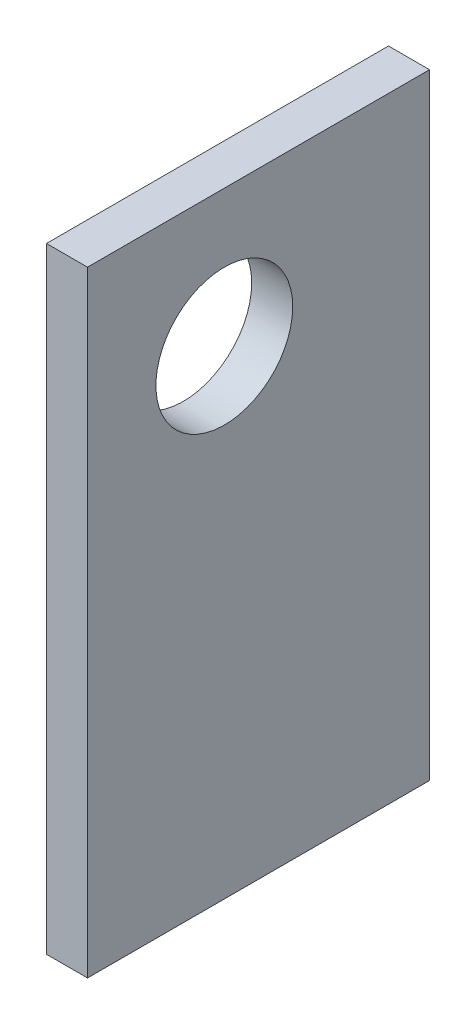
SolidWorks part; units mm, degrees
material "Perspex (TM) GS Acrylic Cast Sheet"
ref_plane "Front Plane" through (0, 0, 0) normal (0, 0, 1) x (1, 0, 0)
ref_plane "Top Plane" through (0, 0, 0) normal (0, 1, 0) x (1, 0, 0)
ref_plane "Right Plane" through (0, 0, 0) normal (1, 0, 0) x (0, 0, -1)
sketch "Sketch1" plane through (0, 0, 0) normal (1, 0, 0) x (0, 0, -1)
  line L2 (-12.5, -22.5) -> (12.5, -22.5)
  line L3 (-12.5, -22.5) -> (-12.5, 22.5)
  line L4 (-12.5, 22.5) -> (12.5, 22.5)
  line L5 (12.5, -22.5) -> (12.5, 22.5)
  line L6 (-12.5, -22.5) -> (12.5, 22.5) construction
  line L7 (-12.5, 22.5) -> (12.5, -22.5) construction
  point P0 (0, -22.5)
  point P1 (0, 0)
  dimension "D1" = 45
  dimension "D2" = 25
extrude "Boss-Extrude1" add sketch "Sketch1" along normal blind 3
sketch "Sketch2" plane through (3, 0, 0) normal (1, 0, 0) x (0, 0, -1)
  line L0 (-12.5, -22.5) -> (12.5, -22.5) construction
  line L1 (-12.5, 22.5) -> (-12.5, -22.5) construction
  circle A0 centre (-2.5, 12.5) radius 5
  point P6 (0, 0)
  point P7 (0, 12.5)
  dimension "D1" = 10
  dimension "D2" = 35
  dimension "D3" = 10
extrude "Cut-Extrude1" cut sketch "Sketch2" against normal blind 3
